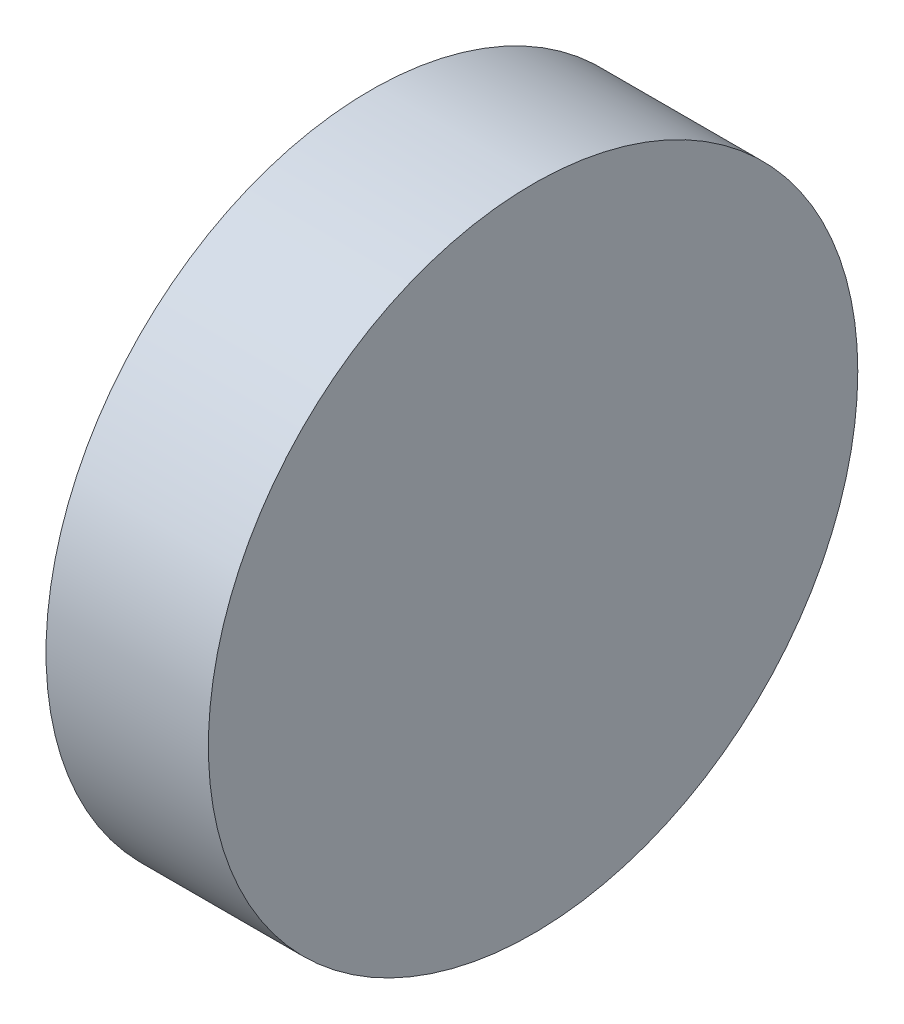
SolidWorks part; units mm, degrees
ref_plane "Front Plane" through (0, 0, 0) normal (0, 0, 1) x (1, 0, 0)
ref_plane "Top Plane" through (0, 0, 0) normal (0, 1, 0) x (1, 0, 0)
ref_plane "Right Plane" through (0, 0, 0) normal (1, 0, 0) x (0, 0, -1)
sketch "Sketch1" plane through (0, 0, 0) normal (1, 0, 0) x (0, 0, -1)
  circle A0 centre (0, 1.3364) radius 200
extrude "Boss-Extrude1" add sketch "Sketch1" along normal blind 100
